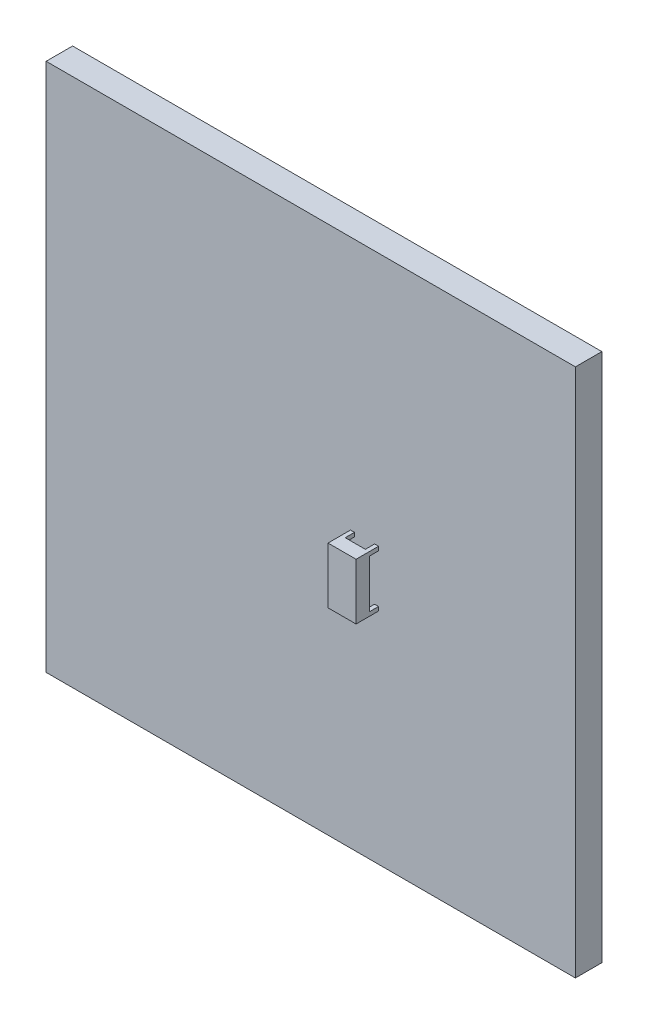
SolidWorks part; units mm, degrees
ref_plane "Front Plane" through (0, 0, 0) normal (0, 0, 1) x (1, 0, 0)
ref_plane "Top Plane" through (0, 0, 0) normal (0, 1, 0) x (1, 0, 0)
ref_plane "Right Plane" through (0, 0, 0) normal (1, 0, 0) x (0, 0, -1)
sketch "Sketch2" plane through (0, 0, 0) normal (0, 0, 1) x (1, 0, 0)
  line L1 (-10000, -10000) -> (10000, -10000)
  line L2 (-10000, -10000) -> (-10000, 10000)
  line L3 (-10000, 10000) -> (10000, 10000)
  line L4 (10000, -10000) -> (10000, 10000)
  line L5 (-10000, -10000) -> (10000, 10000) construction
  line L6 (-10000, 10000) -> (10000, -10000) construction
  point P0 (0, 0)
  dimension "D1" = 20000
  dimension "D2" = 20000
extrude "Boss-Extrude1" add sketch "Sketch2" against normal blind 1000
ref_plane "Plane1" through (0, 0, 350) normal (0, 0, -1) x (-1, 0, 0)
sketch "Sketch6" plane through (0, -650, 350) normal (0, 0, 1) x (1, 0, 0)
  line L1 (1501.8441, -1060.1252) -> (2561.9693, -1060.1252)
  line L2 (1501.8441, -1060.1252) -> (1501.8441, 1060.1252)
  line L3 (1501.8441, 1060.1252) -> (2561.9693, 1060.1252)
  line L4 (2561.9693, -1060.1252) -> (2561.9693, 1060.1252)
  line L5 (1501.8441, -1060.1252) -> (2561.9693, 1060.1252) construction
  line L6 (1501.8441, 1060.1252) -> (2561.9693, -1060.1252) construction
  point P0 (2031.9067, 0)
extrude "Boss-Extrude2" add sketch "Sketch6" along normal blind 500 separate body
sketch "Sketch7" plane through (0, 0, 350) normal (0, 0, -1) x (-1, 0, 0)
  line L1 (-2561.9693, 410.1252) -> (-2411.9693, 410.1252)
  line L2 (-2561.9693, 410.1252) -> (-2561.9693, 260.1252)
  line L3 (-2561.9693, 260.1252) -> (-2411.9693, 260.1252)
  line L4 (-2411.9693, 410.1252) -> (-2411.9693, 260.1252)
  line L5 (-1501.8441, 410.1252) -> (-1651.8441, 410.1252)
  line L6 (-1501.8441, 410.1252) -> (-1501.8441, 260.1252)
  line L7 (-1501.8441, 260.1252) -> (-1651.8441, 260.1252)
  line L8 (-1651.8441, 410.1252) -> (-1651.8441, 260.1252)
  line L9 (-2561.9693, -1710.1252) -> (-2411.9693, -1710.1252)
  line L10 (-2561.9693, -1710.1252) -> (-2561.9693, -1560.1252)
  line L11 (-2561.9693, -1560.1252) -> (-2411.9693, -1560.1252)
  line L12 (-2411.9693, -1710.1252) -> (-2411.9693, -1560.1252)
  line L13 (-1501.8441, -1710.1252) -> (-1651.8441, -1710.1252)
  line L14 (-1501.8441, -1710.1252) -> (-1501.8441, -1560.1252)
  line L15 (-1501.8441, -1560.1252) -> (-1651.8441, -1560.1252)
  line L16 (-1651.8441, -1710.1252) -> (-1651.8441, -1560.1252)
  dimension "D1" = 150
  dimension "D2" = 150
  dimension "D3" = 150
  dimension "D4" = 150
  dimension "D5" = 150
  dimension "D6" = 150
extrude "Boss-Extrude3" add sketch "Sketch7" along normal up to body
